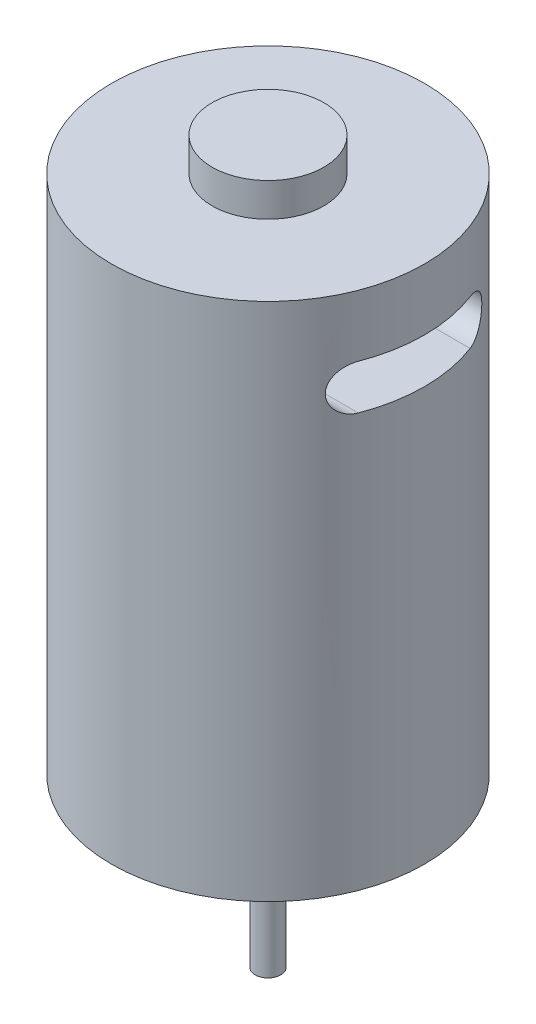
SolidWorks part; units mm, degrees
ref_plane "Front Plane" through (0, 0, 0) normal (0, 0, 1) x (1, 0, 0)
ref_plane "Top Plane" through (0, 0, 0) normal (0, 1, 0) x (1, 0, 0)
ref_plane "Right Plane" through (0, 0, 0) normal (1, 0, 0) x (0, 0, -1)
sketch "Sketch1" plane through (0, 0, 0) normal (1, 0, 0) x (0, 0, -1)
  line L0 (0, 0) -> (1.15, 0)
  line L1 (1.15, 0) -> (1.15, 12)
  line L2 (1.15, 12) -> (5, 12)
  line L3 (5, 12) -> (5, 15)
  line L4 (5, 15) -> (14, 15)
  line L5 (14, 15) -> (14, 61.5)
  line L6 (14, 61.5) -> (5, 61.5)
  line L7 (5, 61.5) -> (5, 64.5)
  line L8 (5, 64.5) -> (0, 64.5)
  line L11 (0, 64.5) -> (0, 0)
  dimension "D1" = 1.15
  dimension "D2" = 12
  dimension "D3" = 5
  dimension "D4" = 14
  dimension "D5" = 46.5
  dimension "D6" = 3
  dimension "D7" = 3
revolve "Revolve1" add sketch "Sketch1" angle 360 about L11
sketch "Sketch2" plane through (0, 15, 0) normal (0, -1, 0) x (1, 0, 0)
  line L0 (-8, 0) -> (8, 0) construction
  line L1 (14, 0) -> (14, 7.1318) construction
  circle A0 centre (0, 0) radius 14 construction
  circle A1 centre (-8, 0) radius 1
  circle A2 centre (8, 0) radius 1
  point P5 (0, 0)
  dimension "D2" = 2
  dimension "D1" = 6
extrude "Cut-Extrude1" cut sketch "Sketch2" against normal blind 5
sketch "Sketch3" plane through (0, 15, 0) normal (0, -1, 0) x (1, 0, 0)
  line L0 (-8.4162, -8.4162) -> (8.4162, 8.4162) construction
  line L1 (-6.364, 6.364) -> (6.364, -6.364) construction
  line L2 (0, 0) -> (14, 0) construction
  arc A0 (-7.8813, 4.3457) -> (-4.3457, 7.8813) centre (0, 0) cw construction
  arc A1 (-5.07, 9.1948) -> (-9.1948, 5.07) centre (0, 0) ccw
  arc A2 (-3.6215, 6.5677) -> (-6.5677, 3.6215) centre (0, 0) ccw
  arc A3 (-3.6215, 6.5677) -> (-5.07, 9.1948) centre (-4.3457, 7.8813) ccw
  arc A4 (-9.1948, 5.07) -> (-6.5677, 3.6215) centre (-7.8813, 4.3457) ccw
  circle A5 centre (0, 0) radius 14 construction
  arc A6 (6.5677, 3.6215) -> (3.6215, 6.5677) centre (0, 0) ccw
  arc A7 (6.5677, 3.6215) -> (9.1948, 5.07) centre (7.8813, 4.3457) ccw
  arc A8 (5.07, 9.1948) -> (3.6215, 6.5677) centre (4.3457, 7.8813) ccw
  arc A9 (9.1948, 5.07) -> (5.07, 9.1948) centre (0, 0) ccw
  arc A10 (4.3457, 7.8813) -> (7.8813, 4.3457) centre (0, 0) cw construction
  arc A11 (3.6215, -6.5677) -> (6.5677, -3.6215) centre (0, 0) ccw
  arc A12 (3.6215, -6.5677) -> (5.07, -9.1948) centre (4.3457, -7.8813) ccw
  arc A13 (9.1948, -5.07) -> (6.5677, -3.6215) centre (7.8813, -4.3457) ccw
  arc A14 (5.07, -9.1948) -> (9.1948, -5.07) centre (0, 0) ccw
  arc A15 (7.8813, -4.3457) -> (4.3457, -7.8813) centre (0, 0) cw construction
  arc A16 (-6.5677, -3.6215) -> (-3.6215, -6.5677) centre (0, 0) ccw
  arc A17 (-6.5677, -3.6215) -> (-9.1948, -5.07) centre (-7.8813, -4.3457) ccw
  arc A18 (-5.07, -9.1948) -> (-3.6215, -6.5677) centre (-4.3457, -7.8813) ccw
  arc A19 (-9.1948, -5.07) -> (-5.07, -9.1948) centre (0, 0) ccw
  arc A20 (-4.3457, -7.8813) -> (-7.8813, -4.3457) centre (0, 0) cw construction
  point P4 (0, 0)
  point P8 (0, 0)
  point P10 (-6.364, 6.364)
  point P25 (6.364, 6.364)
  point P32 (6.364, -6.364)
  point P39 (-6.364, -6.364)
  point P44 (0, 0)
  dimension "D1" = 45
  dimension "D2" = 9
  dimension "D4" = 3
  dimension "D3" = 5
  dimension "D5" = 4
extrude "Cut-Extrude2" cut sketch "Sketch3" against normal blind 5
sketch "Sketch4" plane through (0, 0, 0) normal (1, 0, 0) x (0, 0, -1)
  line L0 (-5, 54) -> (5, 54) construction
  line L1 (-5, 56) -> (5, 56)
  line L2 (-5, 52) -> (5, 52)
  line L3 (0, 61.5) -> (0, 54) construction
  line L4 (14, 61.5) -> (-14, 61.5) construction
  arc A0 (-5, 56) -> (-5, 52) centre (-5, 54) ccw
  arc A1 (5, 52) -> (5, 56) centre (5, 54) ccw
  point P2 (0, 54)
  dimension "D1" = 10
  dimension "D2" = 7.5
  dimension "D3" = 4
extrude "Cut-Extrude3" cut sketch "Sketch4" against normal through all both and the other way through all
